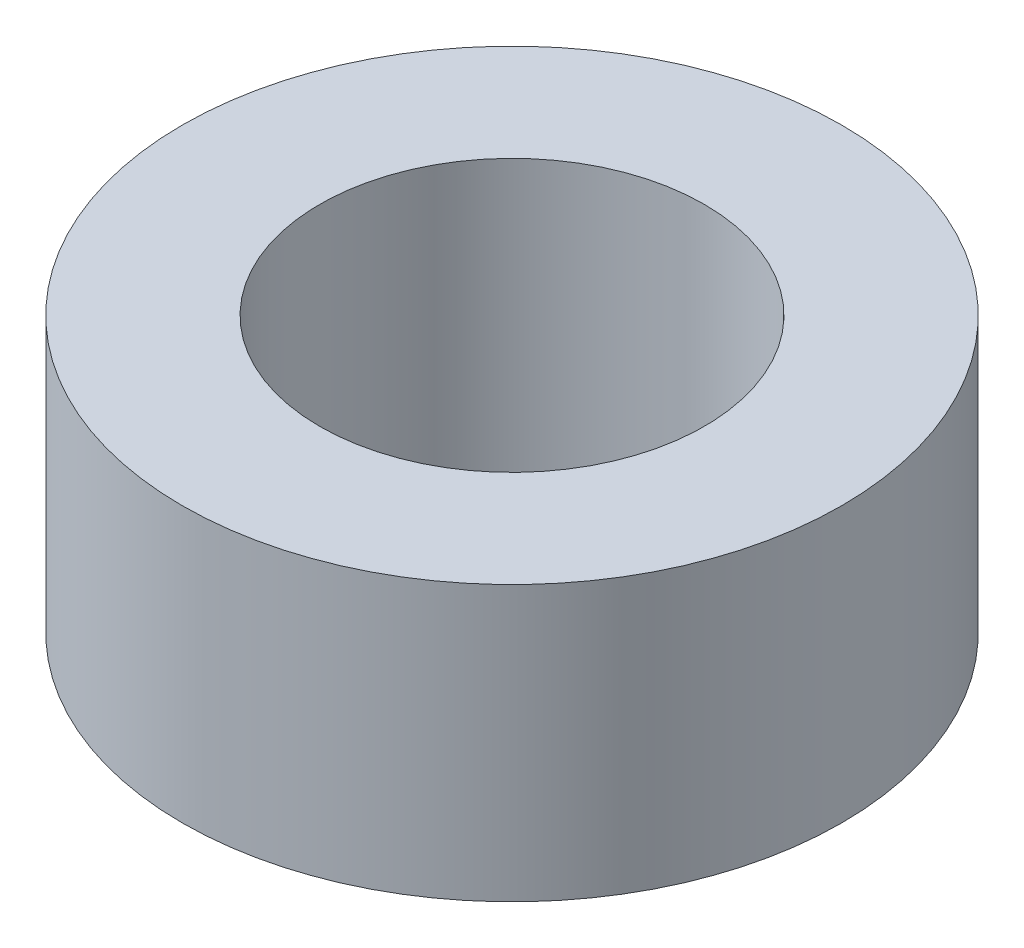
SolidWorks part; units mm, degrees
ref_plane "Front Plane" through (0, 0, 0) normal (0, 0, 1) x (1, 0, 0)
ref_plane "Top Plane" through (0, 0, 0) normal (0, 1, 0) x (1, 0, 0)
ref_plane "Right Plane" through (0, 0, 0) normal (1, 0, 0) x (0, 0, -1)
sketch "Sketch1" plane through (0, 0, 0) normal (0, 1, 0) x (1, 0, 0)
  circle A0 centre (0, 0) radius 3.5
  circle A1 centre (0, 0) radius 6
  dimension "D1" = 12
  dimension "D2" = 7
extrude "Boss-Extrude1" add sketch "Sketch1" along normal blind 5
